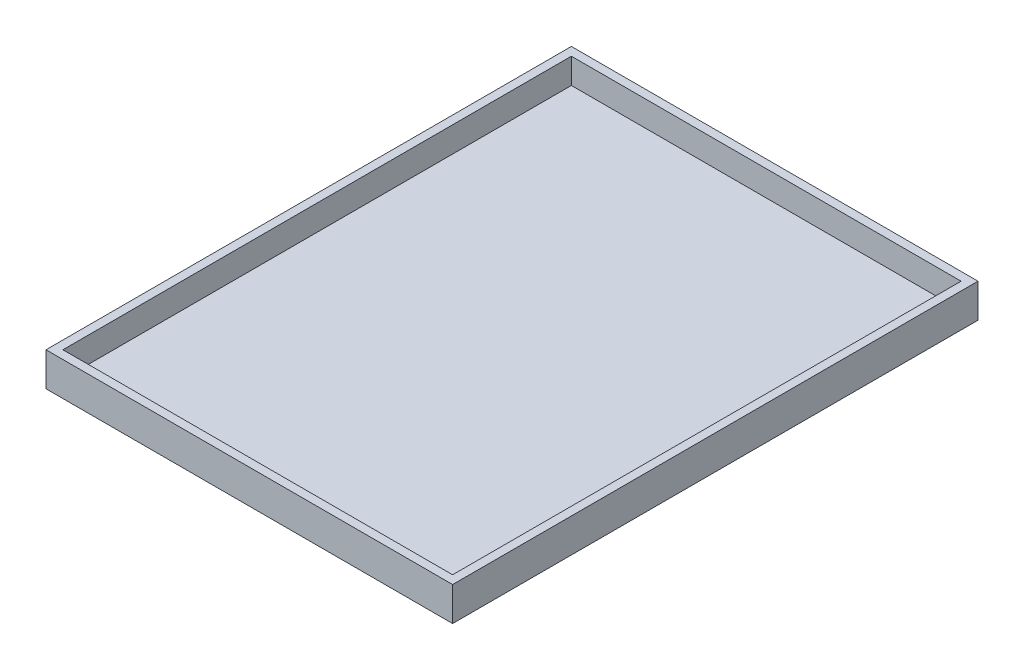
SolidWorks part; units mm, degrees
ref_plane "Front Plane" through (0, 0, 0) normal (0, 0, 1) x (1, 0, 0)
ref_plane "Top Plane" through (0, 0, 0) normal (0, 1, 0) x (1, 0, 0)
ref_plane "Right Plane" through (0, 0, 0) normal (1, 0, 0) x (0, 0, -1)
sketch "Sketch1" plane through (0, 0, 0) normal (0, 1, 0) x (1, 0, 0)
  line L1 (-192.4, 248.6) -> (192.4, 248.6)
  line L2 (-192.4, 248.6) -> (-192.4, -248.6)
  line L3 (-192.4, -248.6) -> (192.4, -248.6)
  line L4 (192.4, 248.6) -> (192.4, -248.6)
  line L5 (-192.4, 248.6) -> (192.4, -248.6) construction
  line L6 (-192.4, -248.6) -> (192.4, 248.6) construction
  point P0 (0, 0)
  dimension "D1" = 497.2
  dimension "D2" = 384.8
extrude "Boss-Extrude1" add sketch "Sketch1" along normal mid plane 8
sketch "Sketch2" plane through (0, 4, 0) normal (0, 1, 0) x (1, 0, 0)
  line L4 (192.4, -248.6) -> (192.4, 248.6)
  line L5 (192.4, 248.6) -> (-192.4, 248.6)
  line L6 (-192.4, 248.6) -> (-192.4, -248.6)
  line L7 (-192.4, -248.6) -> (192.4, -248.6)
  line L8 (192.4, -248.6) -> (192.4, 248.6)
  line L9 (192.4, 248.6) -> (-192.4, 248.6)
  line L10 (-192.4, 248.6) -> (-192.4, -248.6)
  line L11 (-192.4, -248.6) -> (192.4, -248.6)
  line L20 (184.4, -240.6) -> (184.4, 240.6)
  line L21 (184.4, 240.6) -> (-184.4, 240.6)
  line L22 (-184.4, 240.6) -> (-184.4, -240.6)
  line L23 (-184.4, -240.6) -> (184.4, -240.6)
  line L24 (184.4, -240.6) -> (184.4, 240.6)
  line L25 (184.4, 240.6) -> (-184.4, 240.6)
  line L26 (-184.4, 240.6) -> (-184.4, -240.6)
  line L27 (-184.4, -240.6) -> (184.4, -240.6)
  dimension "D1" = 0
  dimension "D2" = 8
extrude "Boss-Extrude2" add sketch "Sketch2" along normal blind 24
